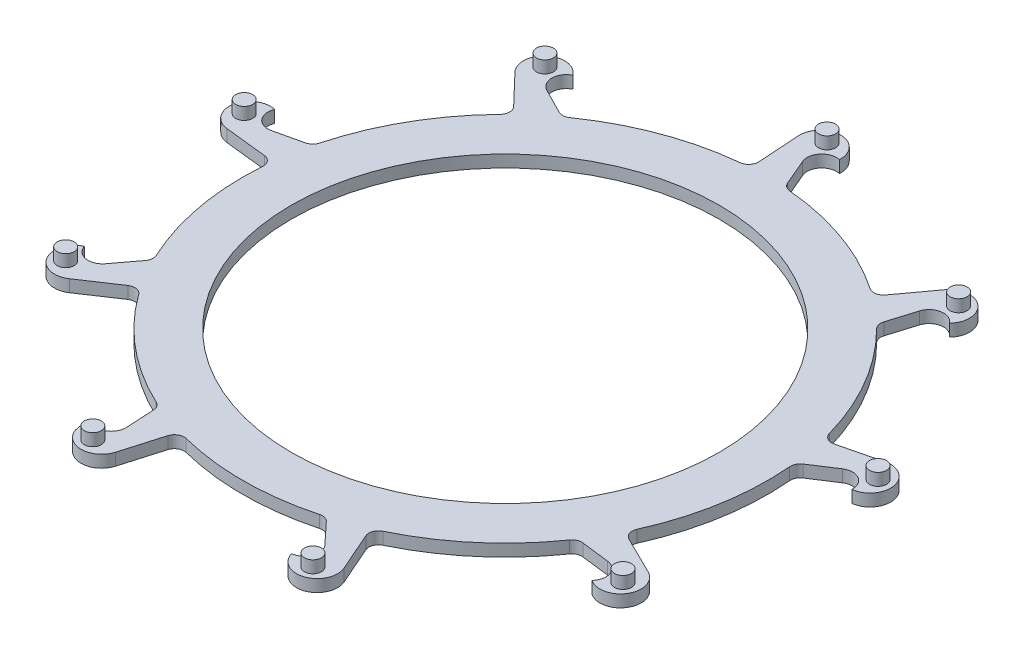
SolidWorks part; units mm, degrees
ref_plane "Front Plane" through (0, 0, 0) normal (0, 0, 1) x (1, 0, 0)
ref_plane "Top Plane" through (0, 0, 0) normal (0, 1, 0) x (1, 0, 0)
ref_plane "Right Plane" through (0, 0, 0) normal (1, 0, 0) x (0, 0, -1)
sketch "Sketch1" plane through (0, 0, 0) normal (0, 1, 0) x (1, 0, 0)
  circle A0 centre (0, 0) radius 55.9594
  circle A1 centre (0, 0) radius 68.6594
  dimension "D1" = 111.9188
  dimension "D2" = 12.7
extrude "Boss-Extrude1" add sketch "Sketch1" along normal blind 3.175
sketch "Sketch2" plane through (0, 3.175, 0) normal (0, 1, 0) x (1, 0, 0)
  line L0 (0, 0) -> (0, 135.9318) construction
  line L1 (0, 0) -> (-4.4905, 68.5124) construction
  line L2 (0, 0) -> (8.8904, 135.6408) construction
  line L3 (-4.6537, 71.0017) -> (-5.3728, 81.9729)
  line L4 (3.8894, 69.9338) -> (0.9836, 76.7774)
  line L5 (-4.6537, 71.0017) -> (-8.8904, 135.6408) construction
  arc A0 (-6.9318, 68.3086) -> (-4.6537, 71.0017) centre (-7.1883, 70.8356) ccw
  circle A1 centre (0, 0) radius 68.6594 construction
  arc A2 (5.3728, 81.9729) -> (-5.3728, 81.9729) centre (0, 82.3251) ccw
  arc A3 (5.3728, 81.9729) -> (0.9836, 76.7774) centre (4.4905, 78.2665) ccw
  arc A4 (6.0052, 68.3963) -> (-6.9318, 68.3086) centre (0, 0) ccw
  arc A5 (3.8894, 69.9338) -> (6.0052, 68.3963) centre (6.2274, 70.9265) ccw
  point P10 (4.4905, 68.5124)
  dimension "D2" = 7.62
  dimension "D3" = 19.05
  dimension "D4" = 5.3843
  dimension "D5" = 5.08
  dimension "D6" = 2.54
  dimension "D7" = 64.77
  dimension "D1" = 7.5
extrude "Boss-Extrude2" add sketch "Sketch2" against normal blind 3.175
pattern_circular "CirPattern1" count 9 over 360 about axis through (0, 0, 0) along (0, 1, 0) of "Boss-Extrude2"
sketch "Sketch3" plane through (0, 3.175, 0) normal (0, 1, 0) x (1, 0, 0)
  line L0 (0, 0) -> (0, 87.7094) construction
  circle A0 centre (0, 84.1322) radius 2.2225
  arc A4 (5.3728, 81.9729) -> (0.9836, 76.7774) centre (4.4905, 78.2665) ccw construction
  arc A5 (5.3728, 81.9729) -> (-5.3728, 81.9729) centre (0, 82.3251) ccw construction
  dimension "D1" = 4.445
  dimension "D2" = 1.3547
  dimension "D3" = 1.3547
sketch "Sketch4" plane through (0, 3.175, 0) normal (0, 1, 0) x (1, 0, 0)
  line L0 (0, 0) -> (0, 105.2172) construction
  line L1 (0, 0) -> (35.9864, 98.8719) construction
  line L2 (21.0579, 57.8562) -> (6.0052, 68.3963) construction
  line L3 (18.2672, 60.4622) -> (6.0052, 68.3963)
  line L4 (24.8709, 58.0587) -> (38.5978, 56.7831)
  arc A0 (38.5978, 56.7831) -> (6.0052, 68.3963) centre (0, 0) ccw construction
  arc A1 (38.5978, 56.7831) -> (6.0052, 68.3963) centre (0, 0) ccw
  arc A2 (5.3728, 81.9729) -> (-5.3728, 81.9729) centre (0, 82.3251) ccw construction
  arc A3 (5.3728, 81.9729) -> (-5.3728, 81.9729) centre (0, 82.3251) ccw construction
  arc A4 (18.2672, 60.4622) -> (24.8709, 58.0587) centre (22.9646, 63.0948) ccw
  dimension "D2" = 75
  dimension "D3" = 5.3848
  dimension "D1" = 20
  dimension "D4" = 14.605
extrude "Cut-Extrude7" [suppressed] cut sketch "Sketch4" against normal through all
pattern_circular "CirPattern12" [suppressed] count 9 over 360
fillet "Fillet1" [suppressed] radius 5.08
extrude "Boss-Extrude3" add sketch "Sketch3" along normal blind 3.175
pattern_circular "CirPattern13" count 9 over 360 about axis through (0, 0, 0) along (0, 1, 0) of "Boss-Extrude3"
